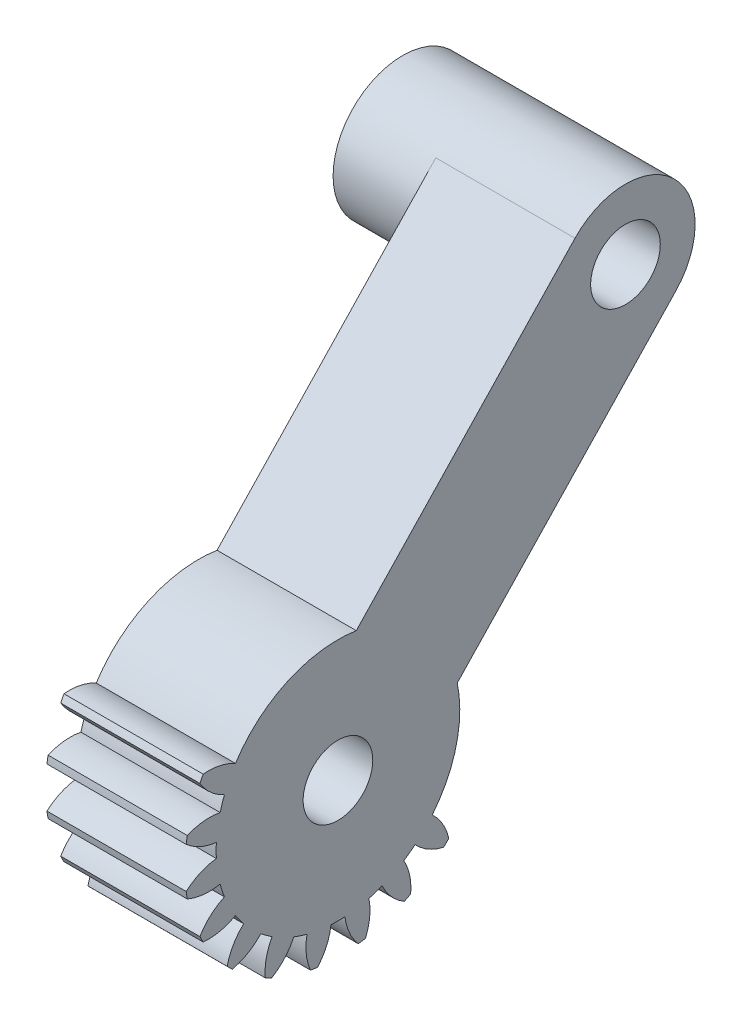
SolidWorks part; units mm, degrees
ref_plane "Front Plane" through (0, 0, 0) normal (0, 0, 1) x (1, 0, 0)
ref_plane "Top Plane" through (0, 0, 0) normal (0, 1, 0) x (1, 0, 0)
ref_plane "Right Plane" through (0, 0, 0) normal (1, 0, 0) x (0, 0, -1)
ref_plane "Plane1" through (4.0439, 0, 0) normal (1, 0, 0) x (0, 0, -1)
sketch "Sketch1" plane through (4.0439, 0, 0) normal (1, 0, 0) x (0, 0, -1)
  circle A0 centre (0.8725, -1.1221) radius 2.5
  arc A1 (-10.0295, 0.3429) -> (-7.8622, -0.6222) centre (-7.392, 3.3501) ccw
  arc A2 (-7.8622, -0.6222) -> (-7.8622, -1.622) centre (0.8725, -1.1221) ccw
  arc A3 (-7.8622, -1.622) -> (-10.0295, -2.587) centre (-7.392, -5.5943) ccw
  arc A4 (-10.0295, -2.587) -> (-9.9487, -3.0977) centre (0.8725, -1.1221) ccw
  arc A5 (-9.9487, -3.0977) -> (-7.5892, -3.3458) centre (-8.3695, 0.5774) ccw
  arc A6 (-7.5892, -3.3458) -> (-7.2802, -4.2967) centre (0.8725, -1.1221) ccw
  arc A7 (-7.2802, -4.2967) -> (-9.0433, -5.8842) centre (-5.6055, -7.9292) ccw
  arc A8 (-9.0433, -5.8842) -> (-8.8085, -6.3449) centre (0.8725, -1.1221) ccw
  arc A9 (-8.8085, -6.3449) -> (-6.4879, -5.8518) centre (-8.4423, -2.3617) ccw
  arc A10 (-6.4879, -5.8518) -> (-5.9002, -6.6607) centre (0.8725, -1.1221) ccw
  arc A11 (-5.9002, -6.6607) -> (-7.0864, -8.7153) centre (-3.185, -9.5979) ccw
  arc A12 (-7.0864, -8.7153) -> (-6.7207, -9.0809) centre (0.8725, -1.1221) ccw
  arc A13 (-6.7207, -9.0809) -> (-4.6661, -7.8948) centre (-7.6033, -5.1795) ccw
  arc A14 (-4.6661, -7.8948) -> (-3.8572, -8.4825) centre (0.8725, -1.1221) ccw
  arc A15 (-3.8572, -8.4825) -> (-4.3504, -10.8031) centre (-0.3672, -10.4369) ccw
  arc A16 (-4.3504, -10.8031) -> (-3.8897, -11.0378) centre (0.8725, -1.1221) ccw
  arc A17 (-3.8897, -11.0378) -> (-2.3022, -9.2748) centre (-5.9347, -7.6001) ccw
  arc A18 (-2.3022, -9.2748) -> (-1.3512, -9.5838) centre (0.8725, -1.1221) ccw
  arc A19 (-1.3512, -9.5838) -> (-1.1032, -11.9432) centre (2.5719, -10.3641) ccw
  arc A20 (-1.1032, -11.9432) -> (-0.5925, -12.0241) centre (0.8725, -1.1221) ccw
  arc A21 (-0.5925, -12.0241) -> (0.3725, -9.8568) centre (-3.5997, -9.3866) ccw
  arc A22 (0.3725, -9.8568) -> (1.3724, -9.8568) centre (0.8725, -1.1221) ccw
  arc A23 (1.3724, -9.8568) -> (2.3374, -12.0241) centre (5.3447, -9.3866) ccw
  arc A24 (2.3374, -12.0241) -> (2.8481, -11.9432) centre (0.8725, -1.1221) ccw
  arc A25 (2.8481, -11.9432) -> (3.0962, -9.5838) centre (-0.827, -10.3641) ccw
  arc A26 (3.0962, -9.5838) -> (4.0471, -9.2748) centre (0.8725, -1.1221) ccw
  arc A27 (4.0471, -9.2748) -> (5.6346, -11.0378) centre (7.6796, -7.6001) ccw
  arc A28 (5.6346, -11.0378) -> (6.0953, -10.8031) centre (0.8725, -1.1221) ccw
  arc A29 (6.0953, -10.8031) -> (5.6022, -8.4825) centre (2.1121, -10.4369) ccw
  arc A30 (5.6022, -8.4825) -> (6.411, -7.8948) centre (0.8725, -1.1221) ccw
  arc A31 (6.411, -7.8948) -> (8.4657, -9.0809) centre (9.3483, -5.1795) ccw
  arc A32 (8.4657, -9.0809) -> (8.8313, -8.7153) centre (0.8725, -1.1221) ccw
  arc A33 (8.8313, -8.7153) -> (7.6451, -6.6607) centre (4.9299, -9.5979) ccw
  arc A34 (7.6451, -6.6607) -> (8.2328, -5.8518) centre (0.8725, -1.1221) ccw
  arc A35 (8.2328, -5.8518) -> (10.5535, -6.3449) centre (10.1873, -2.3617) ccw
  arc A36 (10.5535, -6.3449) -> (10.7882, -5.8842) centre (0.8725, -1.1221) ccw
  arc A37 (10.7882, -5.8842) -> (9.0252, -4.2967) centre (7.3505, -7.9292) ccw
  arc A38 (9.0252, -4.2967) -> (9.3342, -3.3458) centre (0.8725, -1.1221) ccw
  arc A39 (9.3342, -3.3458) -> (11.6936, -3.0977) centre (10.1144, 0.5774) ccw
  arc A40 (11.6936, -3.0977) -> (11.7745, -2.587) centre (0.8725, -1.1221) ccw
  arc A41 (11.7745, -2.587) -> (9.6072, -1.622) centre (9.137, -5.5943) ccw
  arc A42 (9.6072, -1.622) -> (9.6072, -0.6222) centre (0.8725, -1.1221) ccw
  arc A43 (9.6072, -0.6222) -> (11.7745, 0.3429) centre (9.137, 3.3501) ccw
  arc A44 (11.7745, 0.3429) -> (11.6936, 0.8536) centre (0.8725, -1.1221) ccw
  arc A45 (11.6936, 0.8536) -> (9.3342, 1.1016) centre (10.1144, -2.8215) ccw
  arc A46 (9.3342, 1.1016) -> (9.0252, 2.0526) centre (0.8725, -1.1221) ccw
  arc A47 (9.0252, 2.0526) -> (10.7882, 3.6401) centre (7.3505, 5.6851) ccw
  arc A48 (10.7882, 3.6401) -> (10.5535, 4.1008) centre (0.8725, -1.1221) ccw
  arc A49 (10.5535, 4.1008) -> (8.2328, 3.6076) centre (10.1873, 0.1176) ccw
  arc A50 (8.2328, 3.6076) -> (7.6451, 4.4165) centre (0.8725, -1.1221) ccw
  arc A51 (7.6451, 4.4165) -> (8.8313, 6.4711) centre (4.9299, 7.3537) ccw
  arc A52 (8.8313, 6.4711) -> (8.4657, 6.8368) centre (0.8725, -1.1221) ccw
  arc A53 (8.4657, 6.8368) -> (6.411, 5.6506) centre (9.3483, 2.9353) ccw
  arc A54 (6.411, 5.6506) -> (5.6022, 6.2383) centre (0.8725, -1.1221) ccw
  arc A55 (5.6022, 6.2383) -> (6.0953, 8.5589) centre (2.1121, 8.1927) ccw
  arc A56 (6.0953, 8.5589) -> (5.6346, 8.7937) centre (0.8725, -1.1221) ccw
  arc A57 (5.6346, 8.7937) -> (4.0471, 7.0306) centre (7.6796, 5.3559) ccw
  arc A58 (4.0471, 7.0306) -> (3.0962, 7.3396) centre (0.8725, -1.1221) ccw
  arc A59 (3.0962, 7.3396) -> (2.8481, 9.6991) centre (-0.827, 8.1199) ccw
  arc A60 (2.8481, 9.6991) -> (2.3374, 9.7799) centre (0.8725, -1.1221) ccw
  arc A61 (2.3374, 9.7799) -> (1.3724, 7.6126) centre (5.3447, 7.1424) ccw
  arc A62 (1.3724, 7.6126) -> (0.3725, 7.6126) centre (0.8725, -1.1221) ccw
  arc A63 (0.3725, 7.6126) -> (-0.5925, 9.7799) centre (-3.5997, 7.1424) ccw
  arc A64 (-0.5925, 9.7799) -> (-1.1032, 9.6991) centre (0.8725, -1.1221) ccw
  arc A65 (-1.1032, 9.6991) -> (-1.3512, 7.3396) centre (2.5719, 8.1199) ccw
  arc A66 (-1.3512, 7.3396) -> (-2.3022, 7.0306) centre (0.8725, -1.1221) ccw
  arc A67 (-2.3022, 7.0306) -> (-3.8897, 8.7937) centre (-5.9347, 5.3559) ccw
  arc A68 (-3.8897, 8.7937) -> (-4.3504, 8.5589) centre (0.8725, -1.1221) ccw
  arc A69 (-4.3504, 8.5589) -> (-3.8572, 6.2383) centre (-0.3672, 8.1927) ccw
  arc A70 (-3.8572, 6.2383) -> (-4.6661, 5.6506) centre (0.8725, -1.1221) ccw
  arc A71 (-4.6661, 5.6506) -> (-6.7207, 6.8368) centre (-7.6033, 2.9353) ccw
  arc A72 (-6.7207, 6.8368) -> (-7.0864, 6.4711) centre (0.8725, -1.1221) ccw
  arc A73 (-7.0864, 6.4711) -> (-5.9002, 4.4165) centre (-3.185, 7.3537) ccw
  arc A74 (-5.9002, 4.4165) -> (-6.4879, 3.6076) centre (0.8725, -1.1221) ccw
  arc A75 (-6.4879, 3.6076) -> (-8.8085, 4.1008) centre (-8.4423, 0.1176) ccw
  arc A76 (-8.8085, 4.1008) -> (-9.0433, 3.6401) centre (0.8725, -1.1221) ccw
  arc A77 (-9.0433, 3.6401) -> (-7.2802, 2.0526) centre (-5.6055, 5.6851) ccw
  arc A78 (-7.2802, 2.0526) -> (-7.5892, 1.1016) centre (0.8725, -1.1221) ccw
  arc A79 (-7.5892, 1.1016) -> (-9.9487, 0.8536) centre (-8.3695, -2.8215) ccw
  arc A80 (-9.9487, 0.8536) -> (-10.0295, 0.3429) centre (0.8725, -1.1221) ccw
extrude "Boss-Extrude1" add sketch "Sketch1" against normal blind 10
sketch "Sketch2" plane through (4.0439, 0, 0) normal (1, 0, 0) x (0, 0, -1)
  line L0 (0.8725, -1.1221) -> (21.5231, 20.6392) construction
  line L1 (-2.7544, 2.3197) -> (17.8962, 24.0809)
  line L2 (4.4993, -4.5639) -> (25.15, 17.1974)
  line L3 (0.8725, 18.0125) -> (0.8725, -1.1221) construction
  arc A0 (-2.7544, 2.3197) -> (4.4993, -4.5639) centre (0.8725, -1.1221) ccw
  arc A1 (25.15, 17.1974) -> (17.8962, 24.0809) centre (21.5231, 20.6392) ccw
  arc A2 (25.1179, 24.1144) -> (24.8055, 24.4109) centre (21.5231, 20.6392) ccw
  circle A3 centre (21.5231, 20.6392) radius 2.5
  point P3 (11.1978, 9.7585)
  dimension "D2" = 5
  dimension "D1" = 10
  dimension "D3" = 30
  dimension "D4" = 43.5
extrude "Boss-Extrude2" add sketch "Sketch2" against normal blind 10
sketch "Sketch3" plane through (-5.9561, 0, 0) normal (-1, 0, 0) x (0, 0, 1)
  circle A0 centre (-21.5231, 20.6392) radius 2.5
  circle A1 centre (-21.5231, 20.6392) radius 5
extrude "Boss-Extrude3" add sketch "Sketch3" along normal blind 6
sketch "Sketch4" plane through (4.0439, 0, 0) normal (1, 0, 0) x (0, 0, -1)
  circle A1 centre (0.8725, -1.1221) radius 2.5
  dimension "D1" = 5
extrude "Cut-Extrude1" cut sketch "Sketch4" against normal blind 6
sketch "Sketch5" plane through (4.0439, 0, 0) normal (1, 0, 0) x (0, 0, -1)
  circle A0 centre (0.8725, -1.1221) radius 9.5546
sketch "Sketch6" plane through (4.0439, 0, 0) normal (1, 0, 0) x (0, 0, -1)
  line L0 (4.5797, 10.0482) -> (2.1876, 7.5275)
  line L2 (11.8334, 3.1647) -> (9.4414, 0.644)
  line L4 (7.9481, -6.2679) -> (10.3909, -8.0444)
  line L5 (-6.161, 4.0813) -> (-8.5892, 5.8777)
  arc A0 (2.1876, 7.5275) -> (-6.161, 4.0813) centre (0.8725, -1.1221) ccw
  arc A1 (4.5797, 10.0482) -> (-8.5892, 5.8777) centre (0.8725, -1.1221) ccw
  arc A2 (7.9481, -6.2679) -> (9.4414, 0.644) centre (0.8725, -1.1221) ccw
  arc A3 (10.3909, -8.0444) -> (11.8334, 3.1647) centre (0.8725, -1.1221) ccw
extrude "Cut-Extrude2" cut sketch "Sketch6" against normal through all
